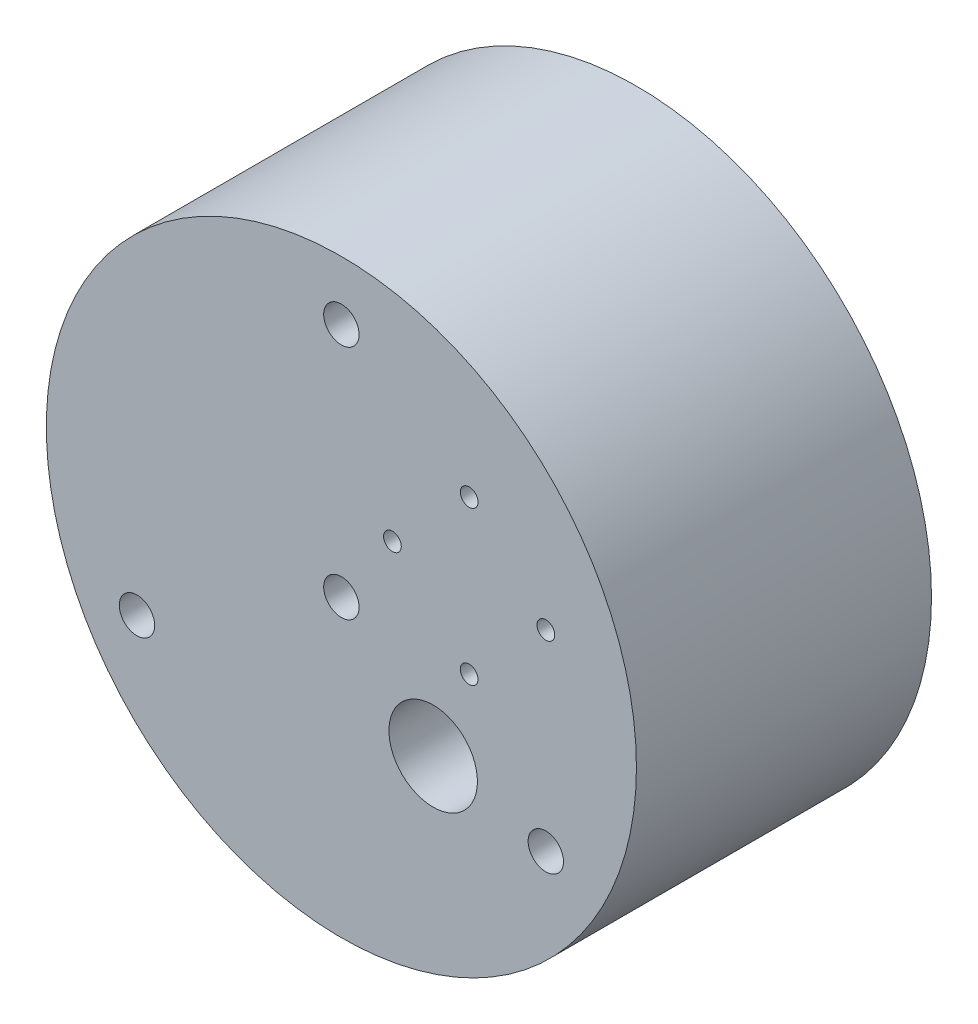
SolidWorks part; units mm, degrees
ref_plane "Front Plane" through (0, 0, 0) normal (0, 0, 1) x (1, 0, 0)
ref_plane "Top Plane" through (0, 0, 0) normal (0, 1, 0) x (1, 0, 0)
ref_plane "Right Plane" through (0, 0, 0) normal (1, 0, 0) x (0, 0, -1)
sketch "Sketch1" plane through (0, 0, 0) normal (0, 0, 1) x (1, 0, 0)
  circle A0 centre (0, 0) radius 50
  dimension "D1" = 100
extrude "Boss-Extrude1" add sketch "Sketch1" along normal blind 50
sketch "Sketch2" plane through (0, 0, 50) normal (0, 0, 1) x (1, 0, 0)
  line L0 (0, 40) -> (0, 0) construction
  line L1 (0, 0) -> (34.641, -20) construction
  line L2 (0, 0) -> (-34.641, -20) construction
  circle A0 centre (0, 0) radius 40 construction
  circle A1 centre (0, 40) radius 3
  circle A2 centre (34.641, -20) radius 3
  circle A3 centre (-34.641, -20) radius 3
  circle A4 centre (0, 0) radius 3
  point P11 (0, 0)
  dimension "D1" = 80
  dimension "D2" = 6
  dimension "D4" = 120
  dimension "D5" = 6
  dimension "D3" = 3
extrude "Cut-Extrude1" cut sketch "Sketch2" against normal through all
sketch "Sketch6" plane through (0, 0, 50) normal (0, 0, 1) x (1, 0, 0)
  line L0 (0, 0) -> (50, 0) construction
  line L1 (21.6506, 12.5) -> (0, 0) construction
  line L2 (21.6506, 12.5) -> (8.6506, 12.5) construction
  line L3 (8.6506, 12.5) -> (34.6506, 12.5) construction
  circle A0 centre (21.6506, 12.5) radius 15 construction
  circle A1 centre (0, 0) radius 50 construction
  circle A2 centre (21.6506, 12.5) radius 11 construction
  circle A3 centre (21.6506, 12.5) radius 9 construction
  circle A4 centre (21.6506, 25.5) radius 1.5
  circle A5 centre (21.6506, 12.5) radius 13 construction
  circle A6 centre (34.6506, 12.5) radius 1.5
  circle A7 centre (21.6506, -0.5) radius 1.5
  circle A8 centre (8.6506, 12.5) radius 1.5
  point P24 (21.6506, 12.5)
  dimension "D1" = 30
  dimension "D6" = 3
  dimension "D2" = 30
  dimension "D3" = 25
  dimension "D7" = 13
  dimension "D4" = 4
  dimension "D5" = 2
  dimension "D8" = 4
extrude "Cut-Extrude2" cut sketch "Sketch6" against normal blind 10
sketch "Sketch7" plane through (0, 0, 50) normal (0, 0, 1) x (1, 0, 0)
  line L0 (0, 0) -> (0, -20.1377) construction
  line L1 (0, 0) -> (15.5563, -15.5563) construction
  circle A0 centre (15.5563, -15.5563) radius 7.5
  dimension "D3" = 15
  dimension "D1" = 45
  dimension "D2" = 22
extrude "Cut-Extrude3" cut sketch "Sketch7" against normal through all
